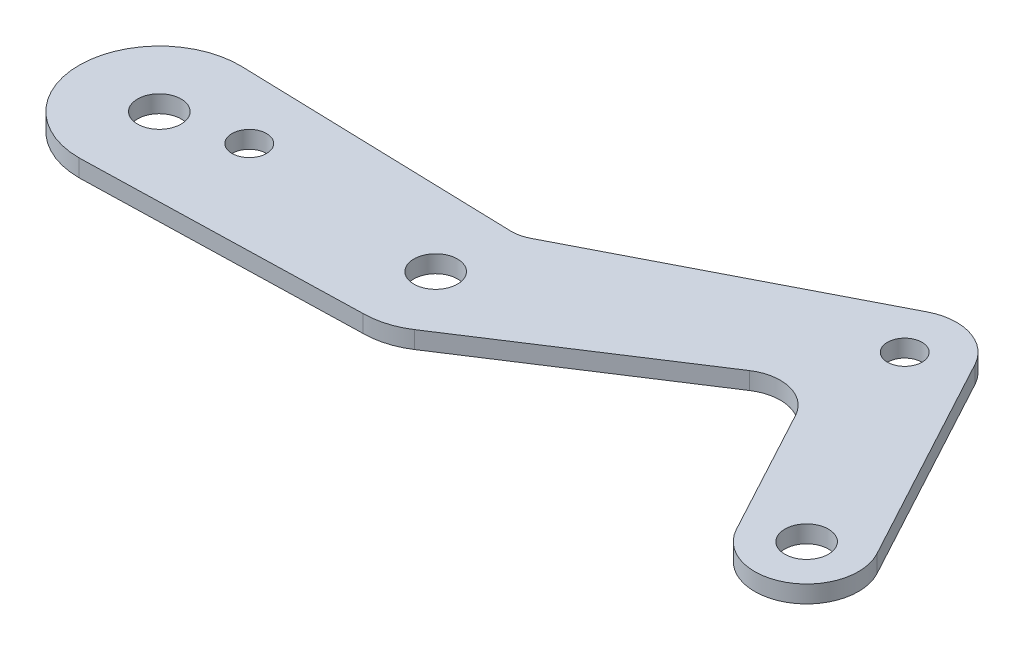
SolidWorks part; units mm, degrees
ref_plane "Front Plane" through (0, 0, 0) normal (0, 0, 1) x (1, 0, 0)
ref_plane "Top Plane" through (0, 0, 0) normal (0, 1, 0) x (1, 0, 0)
ref_plane "Right Plane" through (0, 0, 0) normal (1, 0, 0) x (0, 0, -1)
sketch "Sketch1" plane through (0, 0, 0) normal (0, 1, 0) x (1, 0, 0)
  line L0 (-47.3288, 8.5205) -> (-9.8637, 8.5205) construction
  line L1 (-47.3288, -6.2115) -> (3.4711, -4.8876)
  line L2 (10.7412, -2.7315) -> (48.0387, 21.5246)
  line L3 (72.0739, -4.9648) -> (59.3534, 18.6364)
  line L4 (67.7336, 43.1935) -> (88.841, 4.0775)
  line L5 (55.0016, 47.1442) -> (6.9405, 22.4749)
  line L6 (-46.9025, 23.2463) -> (3.857, 21.7768)
  line L7 (-0.5287, 8.5205) -> (7.471, 8.5205) construction
  line L9 (86.4436, 8.5205) -> (118.2188, 8.5205) construction
  circle A0 centre (-47.3288, 8.5205) radius 4.0005
  circle A2 centre (3.4711, 8.4474) radius 4.0005
  arc A3 (3.4711, -4.8876) -> (10.7412, -2.7315) centre (3.4711, 8.4474) ccw
  circle A4 centre (59.3512, 38.6703) radius 3.175
  arc A5 (67.7336, 43.1935) -> (55.0016, 47.1442) centre (59.3512, 38.6703) ccw
  circle A6 centre (80.4586, -0.4457) radius 4.0005
  arc A7 (72.0739, -4.9648) -> (88.841, 4.0775) centre (80.4586, -0.4457) ccw
  circle A8 centre (-33.9938, 11.6955) radius 3.175
  arc A9 (59.3534, 18.6364) -> (48.0387, 21.5246) centre (52.3662, 14.8705) ccw
  arc A10 (3.857, 21.7768) -> (6.9405, 22.4749) centre (4.0408, 28.1241) ccw
  arc A11 (-46.9025, 23.2463) -> (-46.5615, -6.1915) centre (-47.3288, 8.5205) ccw
  point P29 (0, 0)
  point P30 (0, 0)
  point P31 (77.7373, 40.5688)
  point P32 (0, 0)
  point P35 (0, 0)
  point P36 (0, 0)
  point P37 (0, 0)
  dimension "D1" = 50.8
  dimension "D2" = 6.35
  dimension "D6" = 8.001
  dimension "D7" = 6.35
  dimension "D9" = 26.67
  dimension "D10" = 12.7
  dimension "D13" = 127.7874
  dimension "D14" = 15.875
  dimension "D16" = 19.05
  dimension "D17" = 19.05
  dimension "D3" = 106.68
  dimension "D4" = 3.175
  dimension "D5" = 13.335
  dimension "D8" = 99.695
  dimension "D11" = 8.9662
  dimension "D12" = 30.1498
extrude "Boss-Extrude1" add sketch "Sketch1" against normal blind 3.175 contours L6 A11 L1 A3 L2 A9 L3 A7 L4 A5 L5 A10 A0 A2 A4 A6 A8
